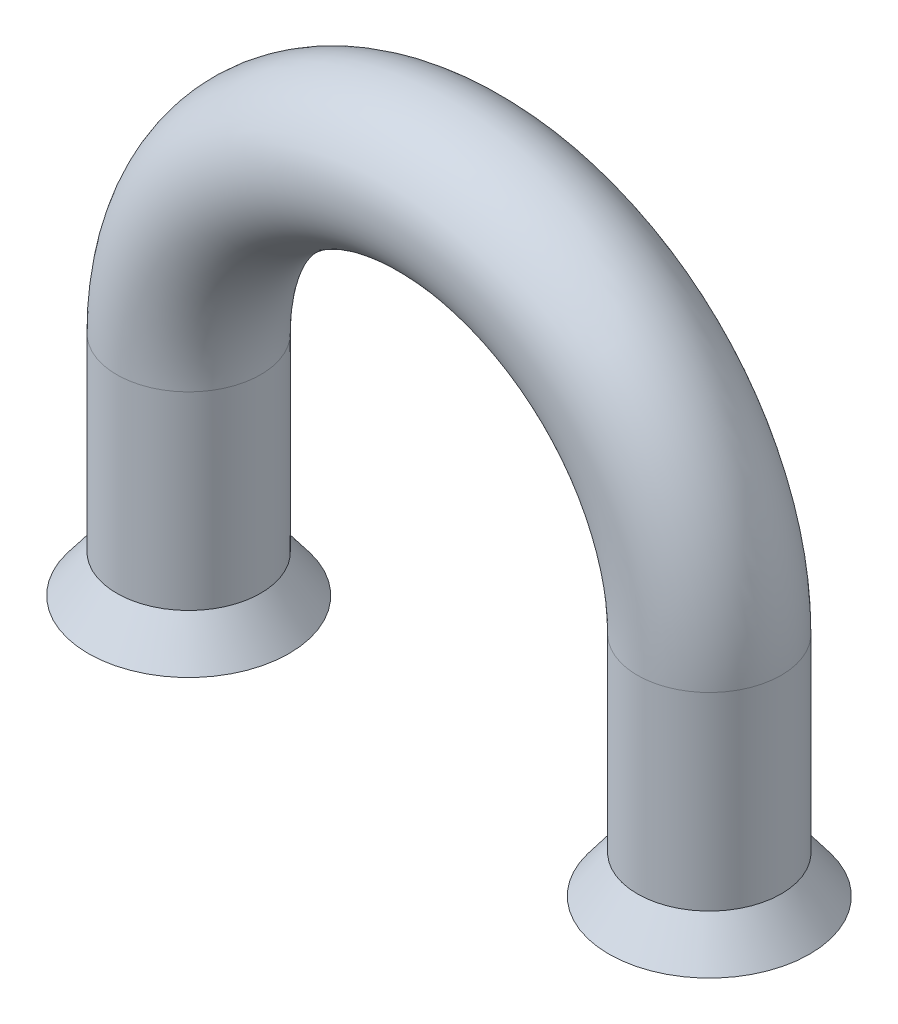
SolidWorks part; units mm, degrees
material "6061-T6 (SS)"
ref_plane "Front Plane" through (0, 0, 0) normal (0, 0, 1) x (1, 0, 0)
ref_plane "Top Plane" through (0, 0, 0) normal (0, 1, 0) x (1, 0, 0)
ref_plane "Right Plane" through (0, 0, 0) normal (1, 0, 0) x (0, 0, -1)
sketch "Sketch1" plane through (0, 0, 0) normal (0, 1, 0) x (1, 0, 0)
  circle A0 centre (0, 0) radius 4.826
  circle A1 centre (0, 0) radius 4.064
  dimension "D1" = 9.652
  dimension "D2" = 8.128
sketch "Sketch2" plane through (0, 0, 0) normal (0, 0, 1) x (1, 0, 0)
  line L0 (0, 0) -> (0, 12.7)
  line L1 (34.925, 12.7) -> (34.925, 0)
  arc A0 (0, 12.7) -> (34.925, 12.7) centre (17.4625, 12.7) cw
  point P5 (0, 0)
  dimension "D1" = 12.7
  dimension "D2" = 34.925
  dimension "D4" = 17.4625
sweep "Sweep1" add profiles "Sketch1" path "Sketch2"
sketch "Sketch3" plane through (0, 0, 0) normal (0, -1, 0) x (1, 0, 0)
  circle A0 centre (0, 0) radius 4.826
  circle A1 centre (0, 0) radius 4.826 construction
extrude "Boss-Extrude1" add sketch "Sketch3" along normal blind 2.54 draft 37 draft outward yes
sketch "Sketch4" plane through (0, -2.54, 0) normal (0, -1, 0) x (1, 0, 0)
  line L0 (-4.826, 0) -> (-4.064, 0) construction
  line L1 (-5.978, 0) -> (-6.74, 0) construction
  circle A0 centre (0, 0) radius 5.978
  circle A1 centre (0, 0) radius 4.826 construction
  circle A2 centre (0, 0) radius 4.064 construction
  circle A3 centre (0, 0) radius 6.74 construction
extrude "Cut-Extrude1" cut sketch "Sketch4" against normal through all draft 37
sketch "Sketch5" plane through (0, 0, 0) normal (0, -1, 0) x (0, 0, -1)
  circle A1 centre (0, 34.925) radius 4.826
  circle A4 centre (0, 34.925) radius 4.826 construction
  point P2 (0, 0)
extrude "Boss-Extrude2" add sketch "Sketch5" along normal blind 2.54 draft 37 draft outward yes
sketch "Sketch6" plane through (0, -2.54, 0) normal (0, -1, 0) x (0, 0, -1)
  line L0 (-5.978, 34.925) -> (-6.74, 34.925) construction
  circle A0 centre (0, 34.925) radius 5.978
  circle A1 centre (0, 34.925) radius 6.74 construction
  dimension "D1" = 0.762
extrude "Cut-Extrude2" cut sketch "Sketch6" against normal through all draft 37
